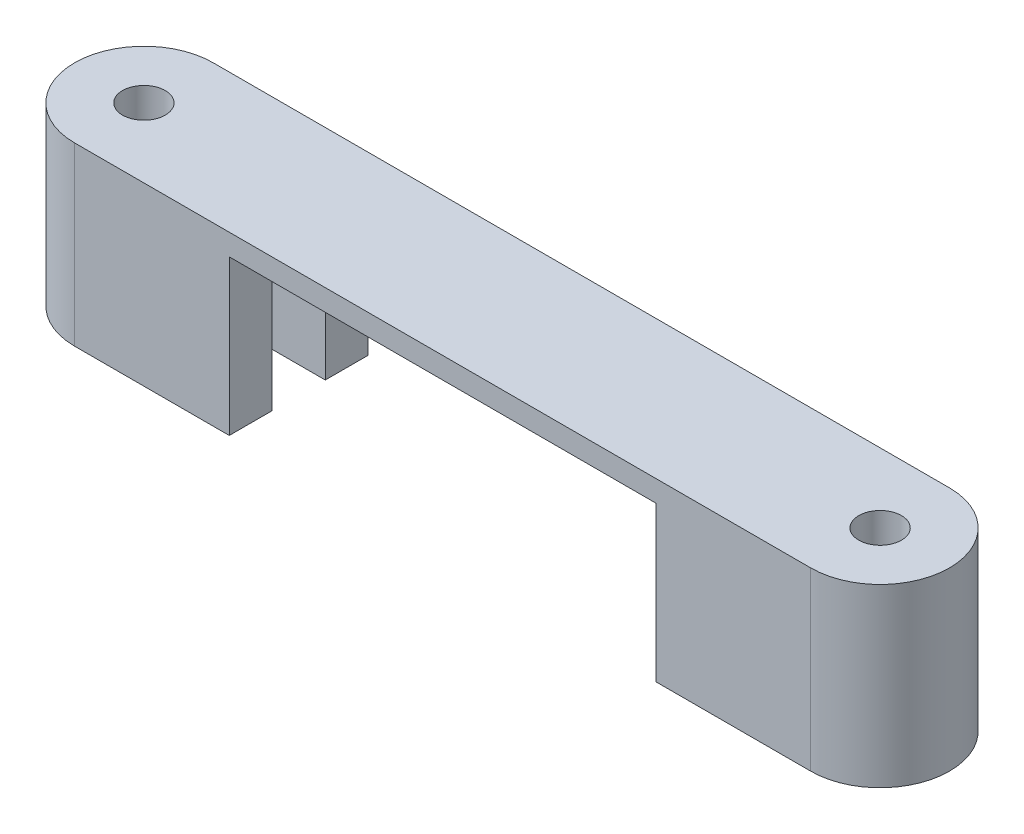
SolidWorks part; units mm, degrees
ref_plane "Plan de face" through (0, 0, 0) normal (0, 0, 1) x (1, 0, 0)
ref_plane "Plan de dessus" through (0, 0, 0) normal (0, 1, 0) x (1, 0, 0)
ref_plane "Plan de droite" through (0, 0, 0) normal (1, 0, 0) x (0, 0, -1)
sketch "Esquisse1" plane through (0, 0, 0) normal (0, 1, 0) x (1, 0, 0)
  line L0 (0, 0) -> (69, 0)
  line L1 (69, 13) -> (0, 13)
  arc A0 (69, 0) -> (69, 13) centre (69, 6.5) ccw
  arc A1 (0, 13) -> (0, 0) centre (0, 6.5) ccw
  dimension "D1" = 69
  dimension "D2" = 13
extrude "Boss.-Extru.1" add sketch "Esquisse1" along normal blind 16.5
sketch "Esquisse2" plane through (0, 16.5, 0) normal (0, 1, 0) x (1, 0, 0)
  circle A0 centre (0, 6.5) radius 2
  circle A1 centre (69, 6.5) radius 2
  dimension "D1" = 4
  dimension "D2" = 4
  dimension "D3" = 69
extrude "Enlèv. mat.-Extru.1" cut sketch "Esquisse2" against normal blind 22
sketch "Esquisse3" plane through (0, 0, 0) normal (0, -1, 0) x (-1, 0, 0)
  line L0 (-54.5, 13) -> (-54.5, 9)
  line L1 (-69, 13) -> (0, 13) construction
  line L2 (-54.5, 9) -> (-62.5, 9)
  line L3 (-62.5, 9) -> (-62.5, 4)
  line L4 (-62.5, 4) -> (-54.5, 4)
  line L5 (-54.5, 4) -> (-54.5, 0)
  line L6 (0, 0) -> (-69, 0) construction
  line L7 (-54.5, 0) -> (-14.5, 0)
  line L8 (-14.5, 0) -> (-14.5, 4)
  line L9 (-14.5, 4) -> (-6.5, 4)
  line L10 (-6.5, 4) -> (-6.5, 9)
  line L11 (-6.5, 9) -> (-14.5, 9)
  line L12 (-14.5, 9) -> (-14.5, 13)
  line L13 (-14.5, 13) -> (-54.5, 13)
  line L14 (-69, 6.5) -> (0, 6.5) construction
  line L15 (-34.5, 6.5) -> (-34.5, 20.9267) construction
  dimension "D1" = 5
  dimension "D2" = 5
  dimension "D3" = 2.5
  dimension "D4" = 2.5
  dimension "D5" = 40
  dimension "D6" = 40
  dimension "D7" = 8
  dimension "D8" = 8
  dimension "D9" = 8
  dimension "D10" = 20
extrude "Enlèv. mat.-Extru.2" cut sketch "Esquisse3" against normal blind 14.5
